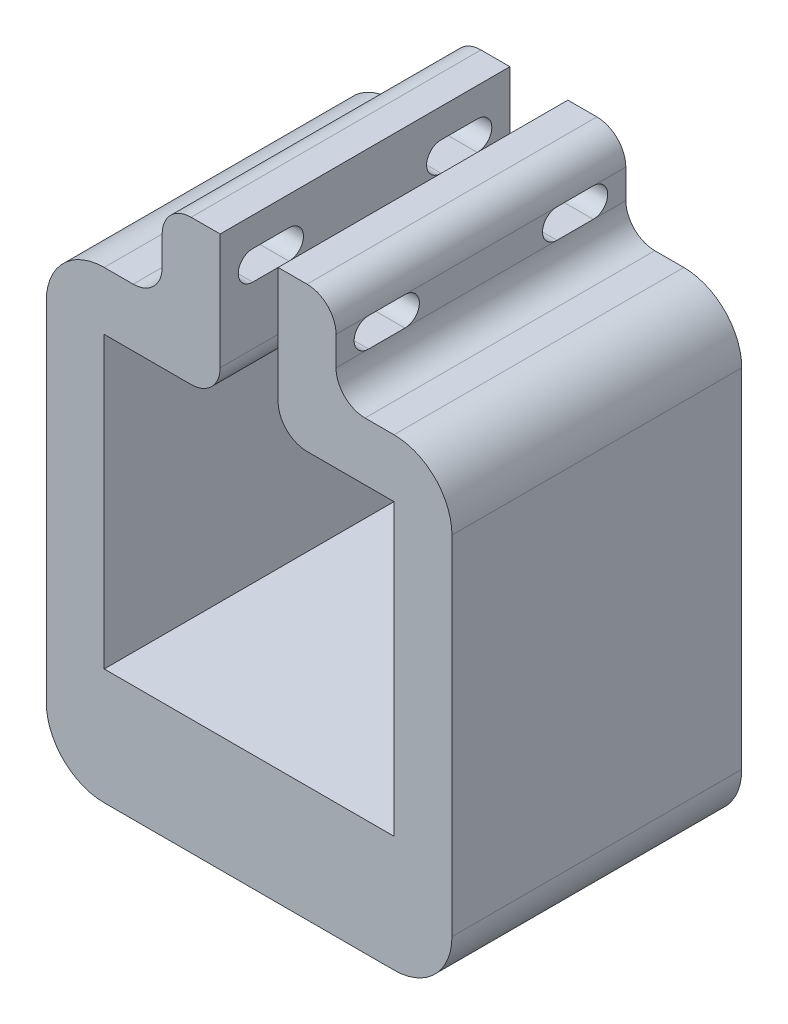
SolidWorks part; units mm, degrees
ref_plane "Front Plane" through (0, 0, 0) normal (0, 0, 1) x (1, 0, 0)
ref_plane "Top Plane" through (0, 0, 0) normal (0, 1, 0) x (1, 0, 0)
ref_plane "Right Plane" through (0, 0, 0) normal (1, 0, 0) x (0, 0, -1)
sketch "Sketch1" plane through (0, 0, 0) normal (0, 0, 1) x (1, 0, 0)
  line L0 (-5.08, 0) -> (-5.08, 25.4)
  line L1 (0, 0) -> (25.4, 0)
  line L2 (0, 0) -> (0, 25.4)
  line L3 (0, 25.4) -> (25.4, 25.4)
  line L4 (25.4, 0) -> (25.4, 25.4)
  line L5 (0, 30.48) -> (25.4, 30.48)
  line L6 (30.48, 0) -> (30.48, 25.4)
  line L7 (0, -5.08) -> (25.4, -5.08)
  line L8 (-5.08, -5.08) -> (30.48, -5.08) construction
  line L9 (30.48, -5.08) -> (30.48, 30.48) construction
  line L10 (-5.08, 30.48) -> (30.48, 30.48) construction
  line L11 (-5.08, -5.08) -> (-5.08, 30.48) construction
  arc A0 (25.4, -5.08) -> (30.48, 0) centre (25.4, 0) ccw
  arc A1 (30.48, 25.4) -> (25.4, 30.48) centre (25.4, 25.4) ccw
  arc A2 (0, 30.48) -> (-5.08, 25.4) centre (0, 25.4) ccw
  arc A3 (0, -5.08) -> (-5.08, 0) centre (0, 0) cw
  dimension "D4" = 5.08
  dimension "D1" = 25.4
  dimension "D2" = 25.4
  dimension "D3" = 5.08
extrude "Boss-Extrude1" add sketch "Sketch1" along normal blind 25.4
sketch "Sketch2" plane through (0, 0, 25.4) normal (0, 0, 1) x (1, 0, 0)
  line L0 (25.4, 30.48) -> (0, 30.48) construction
  line L1 (10.16, 30.48) -> (15.24, 30.48)
  line L2 (10.16, 30.48) -> (10.16, 25.4)
  line L3 (10.16, 25.4) -> (15.24, 25.4)
  line L4 (15.24, 30.48) -> (15.24, 25.4)
  line L5 (25.4, 25.4) -> (0, 25.4) construction
  line L6 (10.16, 25.4) -> (-5.08, 25.4) construction
  line L7 (15.24, 25.4) -> (30.48, 25.4) construction
  dimension "D1" = 5.08
extrude "Cut-Extrude1" cut sketch "Sketch2" against normal through all
fillet "Fillet1" radius 2.54 2 edges at (15.24, 25.4, 12.7) (10.16, 25.4, 12.7)
sketch "Sketch3" plane through (0, 0, 25.4) normal (0, 0, 1) x (1, 0, 0)
  line L1 (10.16, 30.48) -> (5.08, 30.48)
  line L2 (10.16, 30.48) -> (10.16, 38.1)
  line L3 (10.16, 38.1) -> (5.08, 38.1)
  line L4 (5.08, 30.48) -> (5.08, 38.1)
  line L5 (15.24, 30.48) -> (20.32, 30.48)
  line L6 (15.24, 30.48) -> (15.24, 38.1)
  line L7 (15.24, 38.1) -> (20.32, 38.1)
  line L8 (20.32, 30.48) -> (20.32, 38.1)
  dimension "D1" = 5.08
  dimension "D2" = 5.08
  dimension "D3" = 7.62
extrude "Boss-Extrude2" add sketch "Sketch3" against normal up to surface (25.4 mm away) up to face at (12.7, 17.7215, 0)
fillet "Fillet2" radius 2.54 4 edges at (20.32, 30.48, 12.7) (5.08, 30.48, 12.7) (20.32, 38.1, 12.7) (5.08, 38.1, 12.7)
sketch "Sketch4" plane through (5.08, 0, 0) normal (-1, 0, 0) x (0, 0, 1)
  line L0 (2.8575, 34.29) -> (6.0325, 34.29) construction
  line L1 (2.8575, 35.56) -> (6.0325, 35.56)
  line L2 (2.8575, 33.02) -> (6.0325, 33.02)
  line L3 (11.1125, 34.29) -> (14.2875, 34.29) construction
  line L4 (11.1125, 35.56) -> (14.2875, 35.56) construction
  line L5 (11.1125, 33.02) -> (14.2875, 33.02) construction
  line L6 (19.3675, 34.29) -> (22.5425, 34.29) construction
  line L7 (19.3675, 35.56) -> (22.5425, 35.56)
  line L8 (19.3675, 33.02) -> (22.5425, 33.02)
  line L9 (6.0325, 34.29) -> (11.1125, 34.29) construction
  line L10 (14.2875, 34.29) -> (19.3675, 34.29) construction
  line L11 (2.8575, 34.29) -> (0, 34.29) construction
  line L12 (0, 33.02) -> (0, 35.56) construction
  line L13 (22.5425, 34.29) -> (25.4, 34.29) construction
  line L14 (25.4, 35.56) -> (25.4, 33.02) construction
  arc A0 (2.8575, 35.56) -> (2.8575, 33.02) centre (2.8575, 34.29) ccw
  arc A1 (6.0325, 33.02) -> (6.0325, 35.56) centre (6.0325, 34.29) ccw
  arc A2 (11.1125, 35.56) -> (11.1125, 33.02) centre (11.1125, 34.29) ccw construction
  arc A3 (14.2875, 33.02) -> (14.2875, 35.56) centre (14.2875, 34.29) ccw construction
  arc A4 (19.3675, 35.56) -> (19.3675, 33.02) centre (19.3675, 34.29) ccw
  arc A5 (22.5425, 33.02) -> (22.5425, 35.56) centre (22.5425, 34.29) ccw
  point P2 (4.445, 34.29)
  point P9 (12.7, 34.29)
  point P14 (20.955, 34.29)
  dimension "D5" = 1.27
  dimension "D1" = 3.175
  dimension "D2" = 3.175
  dimension "D3" = 3.175
  dimension "D4" = 5.08
extrude "Cut-Extrude2" cut sketch "Sketch4" against normal through all
sketch "Sketch5" plane through (0, -5.08, 0) normal (0, -1, 0) x (1, 0, 0)
  line L1 (-5.08, 25.4) -> (30.48, 25.4)
  line L2 (-5.08, 25.4) -> (-5.08, 0)
  line L3 (-5.08, 0) -> (30.48, 0)
  line L4 (30.48, 25.4) -> (30.48, 0)
extrude "Boss-Extrude3" add sketch "Sketch5" along normal blind 5.08 and the other way up to next (5.08 mm away)
fillet "Fillet3" radius 5.08 2 edges at (30.48, -10.16, 12.7) (-5.08, -10.16, 12.7)
